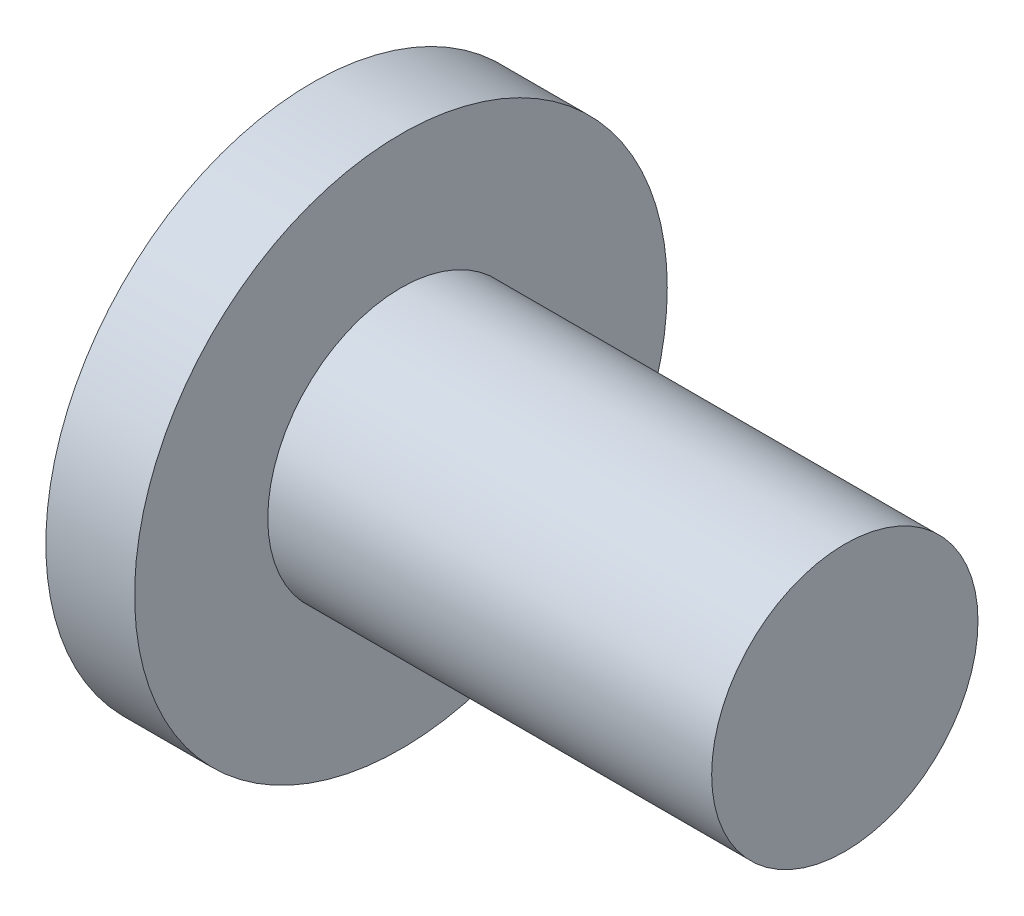
SolidWorks part; units mm, degrees
ref_plane "Front Plane" through (0, 0, 0) normal (0, 0, 1) x (1, 0, 0)
ref_plane "Top Plane" through (0, 0, 0) normal (0, 1, 0) x (1, 0, 0)
ref_plane "Right Plane" through (0, 0, 0) normal (1, 0, 0) x (0, 0, -1)
sketch "Sketch1" plane through (0, 0, 0) normal (0, 1, 0) x (1, 0, 0)
  line L0 (0, 0) -> (-304.8, 0)
  line L1 (-304.8, 0) -> (-304.8, 152.4)
  line L2 (-304.8, 152.4) -> (-254, 152.4)
  line L3 (-254, 152.4) -> (-254, 76.2)
  line L4 (-254, 76.2) -> (0, 76.2)
  line L5 (0, 76.2) -> (0, 0)
  dimension "D1" = 50.8
  dimension "D2" = 254
  dimension "D3" = 76.2
  dimension "D4" = 152.4
revolve "Revolve1" add sketch "Sketch1" angle 360 about L0
